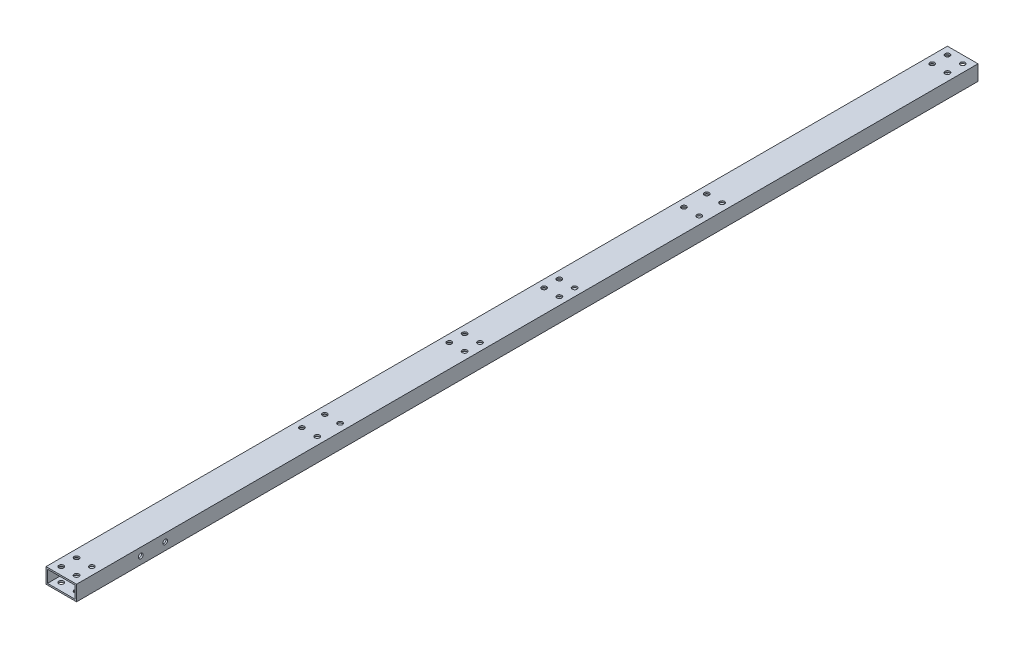
SolidWorks part; units mm, degrees
ref_plane "前视基准面" through (0, 0, 0) normal (0, 0, 1) x (1, 0, 0)
ref_plane "上视基准面" through (0, 0, 0) normal (0, 1, 0) x (1, 0, 0)
ref_plane "右视基准面" through (0, 0, 0) normal (1, 0, 0) x (0, 0, -1)
other "Configuration Table"
sketch "草图1" plane through (0, 0, 0) normal (0, 0, 1) x (1, 0, 0)
  line L1 (0, 0) -> (20, 0)
  line L2 (0, 0) -> (0, -10)
  line L3 (0, -10) -> (20, -10)
  line L4 (20, 0) -> (20, -10)
  dimension "D1" = 20
  dimension "D2" = 10
extrude "拉伸-薄壁1" add sketch "草图1" along normal blind 590 thin
sketch "草图2" plane through (0, -10, 0) normal (0, -1, 0) x (1, 0, 0)
  line L0 (0, 295) -> (20, 295) construction
  line L1 (0, 590) -> (0, 0) construction
  line L2 (20, 590) -> (20, 0) construction
  line L3 (0, 420) -> (20, 420) construction
  line L4 (10, 420) -> (10, 295) construction
  line L5 (0, 170) -> (20, 170) construction
  line L6 (10, 590) -> (10, 580) construction
  line L7 (0, 590) -> (20, 590) construction
  line L8 (10, 580) -> (0, 580) construction
  line L9 (10, 10) -> (0, 10) construction
  line L10 (10, 0) -> (10, 10) construction
  line L11 (0, 326) -> (20, 326) construction
  line L12 (0, 264) -> (20, 264) construction
  circle A0 centre (5, 412.5) radius 1.575
  circle A1 centre (15, 412.5) radius 1.575
  circle A2 centre (15, 427.5) radius 1.575
  circle A3 centre (5, 427.5) radius 1.575
  circle A4 centre (5, 162.5) radius 1.575
  circle A5 centre (15, 162.5) radius 1.575
  circle A6 centre (15, 177.5) radius 1.575
  circle A7 centre (5, 177.5) radius 1.575
  circle A8 centre (5, 585) radius 1.575
  circle A9 centre (15, 585) radius 1.575
  circle A10 centre (15, 575) radius 1.575
  circle A11 centre (5, 575) radius 1.575
  circle A12 centre (5, 15) radius 1.575
  circle A13 centre (15, 15) radius 1.575
  circle A14 centre (15, 5) radius 1.575
  circle A15 centre (5, 5) radius 1.575
  circle A16 centre (5, 331) radius 1.575
  circle A17 centre (15, 331) radius 1.575
  circle A18 centre (5, 321) radius 1.575
  circle A19 centre (15, 321) radius 1.575
  circle A20 centre (15, 269) radius 1.575
  circle A21 centre (5, 269) radius 1.575
  circle A22 centre (15, 259) radius 1.575
  circle A23 centre (5, 259) radius 1.575
  dimension "D2" = 3.15
  dimension "D6" = 3.15
  dimension "D9" = 3.15
  dimension "D1" = 125
  dimension "D3" = 7.5
  dimension "D4" = 5
  dimension "D5" = 10
  dimension "D7" = 5
  dimension "D8" = 5
  dimension "D10" = 31
  dimension "D11" = 5
  dimension "D12" = 5
extrude "切除-拉伸1" cut sketch "草图2" against normal through all
sketch "草图3" plane through (0, 0, 0) normal (-1, 0, 0) x (0, 0, 1)
  line L0 (540, 0) -> (540, -10) construction
  line L1 (590, 0) -> (0, 0) construction
  line L2 (590, -10) -> (0, -10) construction
  line L3 (590, 0) -> (590, -10) construction
  line L4 (590, -5) -> (0, -5) construction
  line L5 (0, 0) -> (0, -10) construction
  circle A0 centre (548, -5) radius 1.575
  circle A1 centre (532, -5) radius 1.575
  dimension "D2" = 3.15
  dimension "D1" = 50
  dimension "D3" = 8
extrude "切除-拉伸2" cut sketch "草图3" against normal through all
